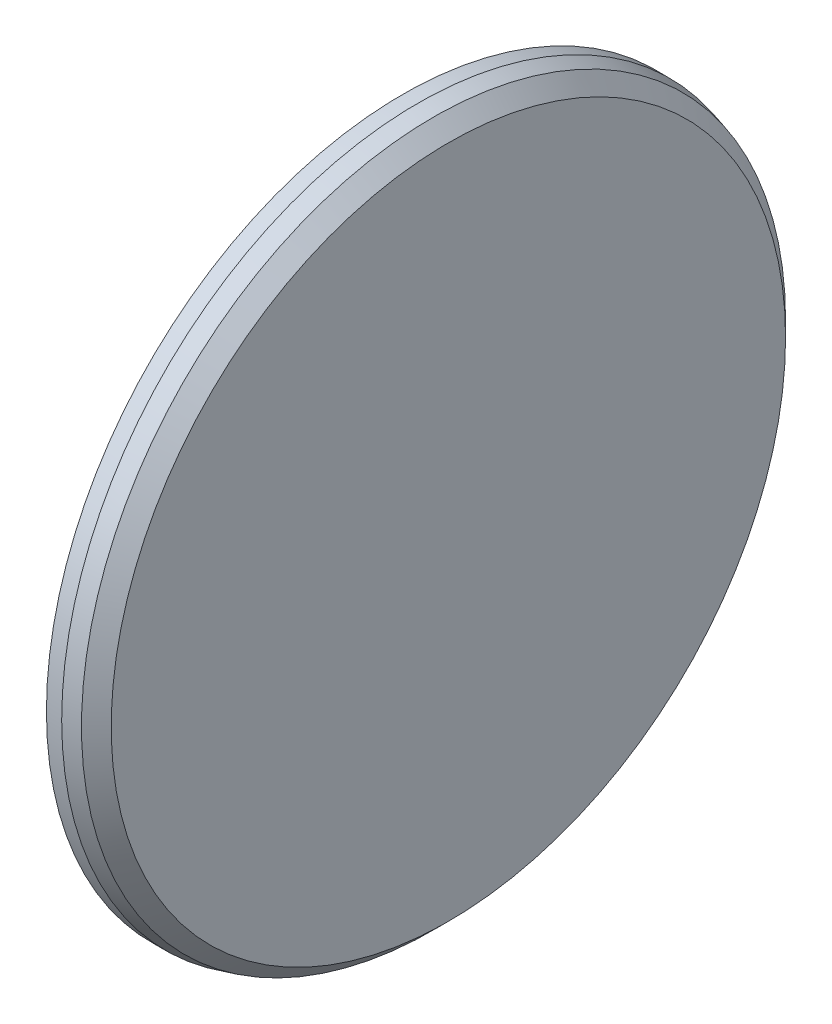
SolidWorks part; units mm, degrees
material "1060 Alloy"
ref_plane "Front Plane" through (0, 0, 0) normal (0, 0, 1) x (1, 0, 0)
ref_plane "Top Plane" through (0, 0, 0) normal (0, 1, 0) x (1, 0, 0)
ref_plane "Right Plane" through (0, 0, 0) normal (1, 0, 0) x (0, 0, -1)
sketch "Sketch1" plane through (0, 0, 0) normal (0, 1, 0) x (1, 0, 0)
  line L0 (0, 8.7884) -> (0, -50.1399) construction
  line L1 (-30, 8.7884) -> (-30, -36.2116)
  line L2 (30, -16.2116) -> (30, -36.2116)
  line L3 (-30, 8.7884) -> (-10, 8.7884)
  line L4 (-10, 8.7884) -> (10.4904, 3.298)
  line L5 (10.4904, 3.298) -> (30, -16.2116)
  line L6 (-30, -36.2116) -> (0, -36.2116)
  line L7 (30, -36.2116) -> (30, -458.7116)
  line L8 (0, -36.2116) -> (0, -358.7116)
  line L9 (0, -358.7116) -> (-50, -358.7116)
  line L10 (-50, -358.7116) -> (-50, -458.7116)
  line L11 (-170.9666, -458.7116) -> (174.9616, -458.7116) construction
  line L12 (30, -458.7116) -> (-50, -458.7116)
  dimension "D1" = 60
  dimension "D2" = 20
  dimension "D4" = 45
  dimension "D5" = 45
  dimension "D6" = 442.5
  dimension "D7" = 467.5
  dimension "D8" = 100
  dimension "D9" = 80
  dimension "D3" = 15
revolve "Revolve2" add sketch "Sketch1" angle 360 about L12
sketch "Sketch3" plane through (0, 0, 0) normal (-1, 0, 0) x (0, 0, 1)
  line L0 (458.7116, 467.5) -> (458.7116, -467.5) construction
  line L1 (438.7116, 353.5622) -> (438.7116, 105.8301)
  line L2 (478.7116, 411.4076) -> (478.7116, 105.8301)
  line L3 (738.4802, 302.3008) -> (542.0587, 68.2148)
  line L4 (670.6561, 283.7001) -> (511.417, 93.9263)
  line L5 (867.342, 51.744) -> (566.4068, -1.319)
  line L6 (803.4295, 81.0916) -> (559.4609, 38.0734)
  line L7 (805.0011, -223.0243) -> (540.3631, -70.2355)
  line L8 (774.9055, -159.4606) -> (560.3631, -35.5945)
  line L9 (580.6275, -393.4371) -> (476.1138, -106.2881)
  line L10 (598.4309, -325.3994) -> (513.7015, -92.6073)
  line L11 (299.2081, -379.7563) -> (403.7217, -92.6073)
  line L12 (356.5801, -339.0802) -> (441.3095, -106.2881)
  line L13 (92.4221, -188.3833) -> (357.0601, -35.5945)
  line L14 (162.5177, -194.1016) -> (377.0601, -70.2355)
  line L15 (57.0271, 91.1363) -> (357.9623, 38.0734)
  line L16 (107.0478, 41.6993) -> (351.0164, -1.319)
  line L17 (209.5848, 328.0123) -> (406.0063, 93.9263)
  line L18 (216.1253, 257.9886) -> (375.3645, 68.2148)
  circle A0 centre (458.7116, 0) radius 467.5 construction
  arc A1 (438.7116, 105.8301) -> (431.4389, 96.2091) centre (428.7116, 105.8301) cw
  circle A2 centre (458.7116, 0) radius 100 construction
  arc A3 (478.7116, 411.4076) -> (489.4389, 421.3812) centre (488.7116, 411.4076) cw
  circle A4 centre (458.7116, 0) radius 422.5 construction
  circle A5 centre (458.7116, 0) radius 422.5 construction
  arc A6 (438.7116, 353.5622) -> (365.4702, 412.0829) centre (378.7116, 353.5622) ccw
  circle A7 centre (458.7116, 0) radius 100 construction
  arc A8 (478.7116, 105.8301) -> (485.9843, 96.2091) centre (488.7116, 105.8301) ccw
  arc A9 (365.4702, 412.0829) -> (489.4389, 421.3812) centre (458.7116, 0) cw
  arc A10 (431.4389, 96.2091) -> (485.9843, 96.2091) centre (458.7116, 0) cw
  arc A11 (652.1663, 375.6082) -> (753.1087, 303.0456) centre (458.7116, 0) cw
  arc A12 (738.4802, 302.3008) -> (753.1087, 303.0456) centre (746.1407, 295.8729) cw
  arc A13 (670.6561, 283.7001) -> (652.1663, 375.6082) centre (624.6935, 322.2674) ccw
  arc A14 (511.417, 93.9263) -> (499.6615, 91.231) centre (503.7565, 100.3542) cw
  arc A15 (542.0587, 68.2148) -> (541.4458, 56.1699) centre (549.7192, 61.7869) ccw
  arc A16 (848.3428, 163.3823) -> (879.0268, 42.9116) centre (458.7116, 0) cw
  arc A17 (867.342, 51.744) -> (879.0268, 42.9116) centre (869.0785, 41.896) cw
  arc A18 (803.4295, 81.0916) -> (848.3428, 163.3823) centre (793.0106, 140.1801) ccw
  arc A19 (559.4609, 38.0734) -> (548.7233, 43.5649) centre (557.7244, 47.9214) cw
  arc A20 (566.4068, -1.319) -> (558.195, -10.1519) centre (568.1433, -11.167) ccw
  arc A21 (862.2065, -125.292) -> (808.2748, -237.3012) centre (458.7116, 0) cw
  arc A22 (805.0011, -223.0243) -> (808.2748, -237.3012) centre (800.0011, -231.6846) cw
  arc A23 (774.9055, -159.4606) -> (862.2065, -125.292) centre (804.9055, -107.4991) ccw
  arc A24 (560.3631, -35.5945) -> (555.6675, -24.4857) centre (565.3631, -26.9343) cw
  arc A25 (540.3631, -70.2355) -> (528.3948, -71.7234) centre (535.3631, -78.8958) ccw
  arc A26 (687.2705, -355.3408) -> (573.9583, -406.4781) centre (458.7116, 0) cw
  arc A27 (580.6275, -393.4371) -> (573.9583, -406.4781) centre (571.2305, -396.8573) cw
  arc A28 (598.4309, -325.3994) -> (687.2705, -355.3408) centre (654.8124, -304.8782) ccw
  arc A29 (513.7015, -92.6073) -> (517.2451, -81.0792) centre (523.0984, -89.1871) cw
  arc A30 (476.1138, -106.2881) -> (465.9891, -99.7348) centre (466.7168, -109.7083) ccw
  arc A31 (405.3892, -419.1217) -> (285.7166, -385.4594) centre (458.7116, 0) cw
  arc A32 (299.2081, -379.7563) -> (285.7166, -385.4594) centre (289.8111, -376.3361) cw
  arc A33 (356.5801, -339.0802) -> (405.3892, -419.1217) centre (412.9616, -359.6014) ccw
  arc A34 (441.3095, -106.2881) -> (451.4341, -99.7348) centre (450.7064, -109.7083) cw
  arc A35 (403.7217, -92.6073) -> (400.1782, -81.0792) centre (394.3248, -89.1871) ccw
  arc A36 (148.4581, -286.7908) -> (78.4212, -184.08) centre (458.7116, 0) cw
  arc A37 (92.4221, -188.3833) -> (78.4212, -184.08) centre (87.4221, -179.7231) cw
  arc A38 (162.5177, -194.1016) -> (148.4581, -286.7908) centre (192.5177, -246.0631) ccw
  arc A39 (377.0601, -70.2355) -> (389.0284, -71.7234) centre (382.0601, -78.8958) cw
  arc A40 (357.0601, -35.5945) -> (361.7557, -24.4857) centre (352.0601, -26.9343) ccw
  arc A41 (36.698, -20.2674) -> (49.0679, 103.4325) centre (458.7116, 0) cw
  arc A42 (57.0271, 91.1363) -> (49.0679, 103.4325) centre (58.7636, 100.9844) cw
  arc A43 (107.0478, 41.6993) -> (36.698, -20.2674) centre (96.6289, -17.3892) ccw
  arc A44 (351.0164, -1.319) -> (359.2282, -10.1519) centre (349.2799, -11.167) cw
  arc A45 (357.9623, 38.0734) -> (368.7, 43.5649) centre (359.6988, 47.9214) ccw
  arc A46 (122.4028, 255.7394) -> (211.3915, 342.5478) centre (458.7116, 0) cw
  arc A47 (209.5848, 328.0123) -> (211.3915, 342.5478) centre (217.2452, 334.4402) cw
  arc A48 (216.1253, 257.9886) -> (122.4028, 255.7394) centre (170.1626, 219.4214) ccw
  arc A49 (375.3645, 68.2148) -> (375.9774, 56.1699) centre (367.704, 61.7869) cw
  arc A50 (406.0063, 93.9263) -> (417.7617, 91.231) centre (413.6667, 100.3542) ccw
  point P28 (-83.4996, 755.1723)
  point P29 (482.5762, 41.9478)
  point P133 (458.7116, 0)
  point P134 (458.7116, 0)
  dimension "D2" = 10
  dimension "D3" = 60
  dimension "D4" = 10
  dimension "D5" = 10
  dimension "D1" = 40
  dimension "D6" = 9
extrude "Boss-Extrude2" add sketch "Sketch3" along normal blind 20 contours A50 L17 A47 A15 A48 L18 A49 | A45 L15 A42 A15 A43 L16 A44 A50 | A40 L13 A37 A15 A38 L14 A39 A50 | A35 L11 A32 A15 A33 L12 A34 A50 | A30 L9 A27 A15 A28 L10 A29 A50 | A25 L7 A22 A15 A23 L8 A24 A50 | A20 L5 A17 A15 A18 L6 A19 A50 | A15 L3 A12 A13 L4 A14 A50 | L1 A1 A10 A8 L2 A3 A9 A6
equation "\"A\"= 60mm"
equation "\"B\"= 935mm"
equation "\"D1@Sketch1\"=\"A\""
equation "\"D6@Sketch1\"=(\"B\"-50)/2"
equation "\"D7@Sketch1\"=\"B\"/2"
equation "\"D9@Sketch1\"=\"A\"+20"
